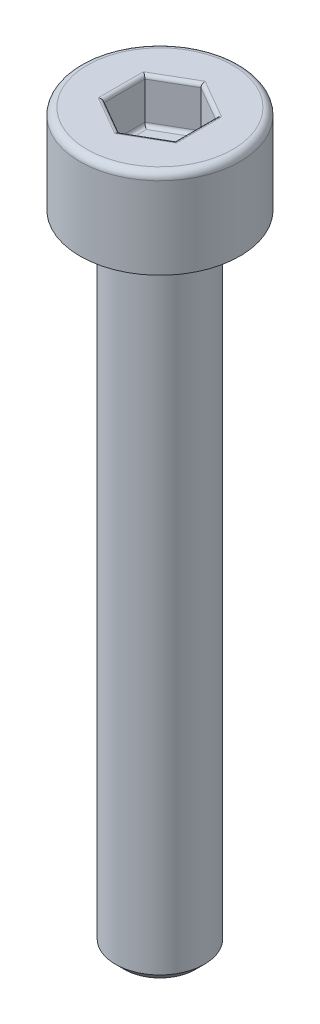
SolidWorks part; units mm, degrees
ref_plane "Front Plane" through (0, 0, 0) normal (0, 0, 1) x (1, 0, 0)
ref_plane "Top Plane" through (0, 0, 0) normal (0, 1, 0) x (1, 0, 0)
ref_plane "Right Plane" through (0, 0, 0) normal (1, 0, 0) x (0, 0, -1)
sketch "Sketch1" plane through (0, 0, 0) normal (0, 0, 1) x (1, 0, 0)
  line L0 (0, 0) -> (0, -47.0967) construction
  line L1 (0, -20.5) -> (-1.25, -20.5)
  line L2 (-1.25, -20.5) -> (-1.25, -2.5)
  line L3 (-1.25, -2.5) -> (-2.25, -2.5)
  line L4 (-2.25, -2.5) -> (-2.25, 0)
  line L5 (-2.25, 0) -> (0, 0)
  line L6 (0, 0) -> (0, -20.5)
  dimension "d" = 2.5
  dimension "l" = 20.5
  dimension "k" = 2.5
  dimension "dk" = 4.5
revolve "Revolve1" add sketch "Sketch1" angle 360 about L0
chamfer "Chamfer1" distance 0.25 angle 45 2 edges at (0, -2.5, 1.25) (0, -20.5, 1.25)
fillet "Fillet1" radius 0.2 1 edges at (0, 0, 2.25)
sketch "Sketch2" plane through (0, 0, 0) normal (0, 1, 0) x (1, 0, 0)
  line L1 (0, 1.1547) -> (-1, 0.5774)
  line L2 (-1, 0.5774) -> (-1, -0.5774)
  line L3 (-1, -0.5774) -> (0, -1.1547)
  line L4 (0, -1.1547) -> (1, -0.5774)
  line L5 (1, -0.5774) -> (1, 0.5774)
  line L6 (1, 0.5774) -> (0, 1.1547)
  circle A0 centre (0, 0) radius 1 construction
  dimension "s" = 2
extrude "Cut-Extrude1" cut sketch "Sketch2" against normal blind 1.25
fillet "Fillet2" radius 0.1 12 edges at (-0.5, 0, -0.866) (-1, 0, 0) (-0.5, 0, 0.866) (0.5, 0, 0.866) (1, 0, 0) (0.5, 0, -0.866) (1, -1.25, 0) (0.5, -1.25, 0.866) (-0.5, -1.25, 0.866) (-1, -1.25, 0) (-0.5, -1.25, -0.866) (0.5, -1.25, -0.866)
